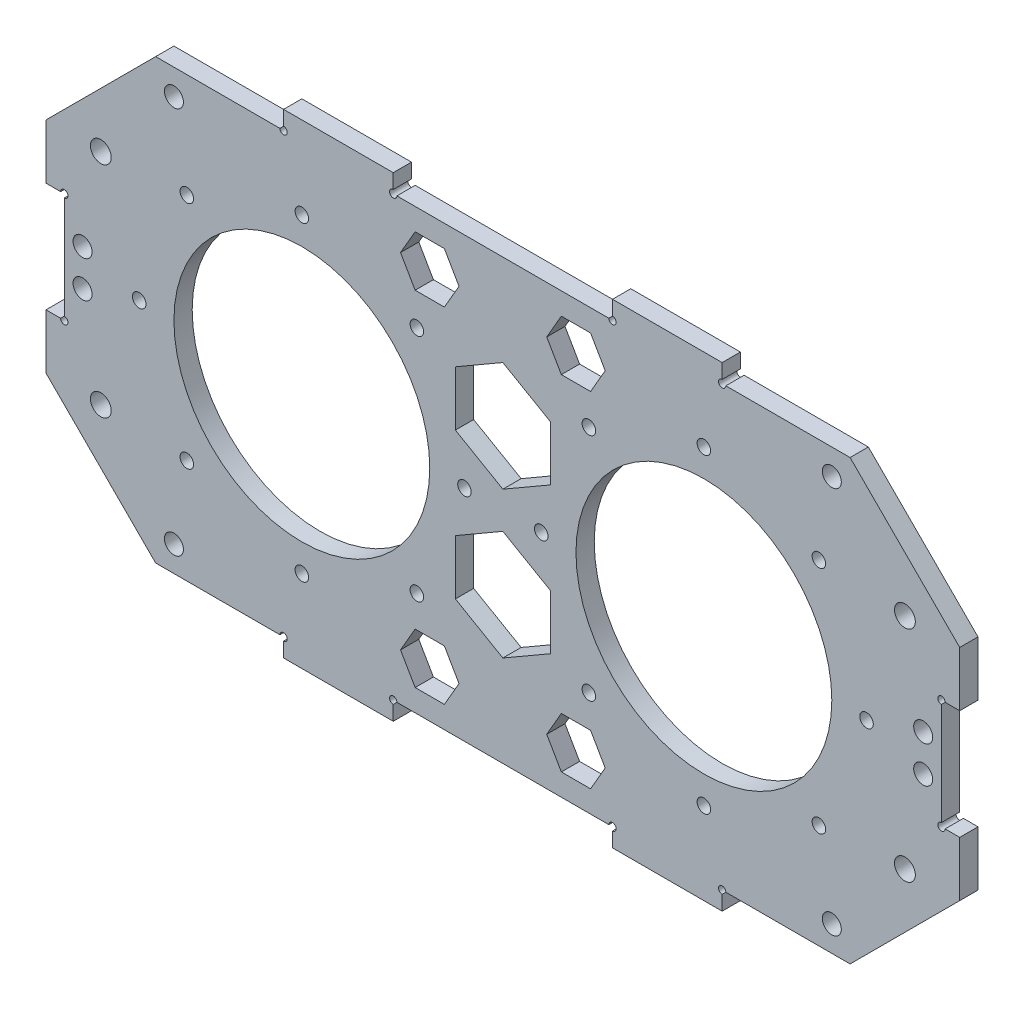
SolidWorks part; units mm, degrees
ref_plane "前视基准面" through (0, 0, 0) normal (0, 0, 1) x (1, 0, 0)
ref_plane "上视基准面" through (0, 0, 0) normal (0, 1, 0) x (1, 0, 0)
ref_plane "右视基准面" through (0, 0, 0) normal (1, 0, 0) x (0, 0, -1)
other "Configuration Table"
sketch "草图1" plane through (0, 0, 0) normal (0, 0, 1) x (1, 0, 0)
  line L1 (0, 0) -> (250, 0)
  line L2 (0, 0) -> (0, 120)
  line L3 (0, 120) -> (250, 120)
  line L4 (250, 0) -> (250, 120)
  circle A0 centre (70, 60) radius 35
  circle A1 centre (180, 60) radius 35
  dimension "D3" = 70
  dimension "D4" = 70
  dimension "D7" = 70
  dimension "D8" = 60
  dimension "D1" = 250
  dimension "D2" = 120
  dimension "D5" = 60
  dimension "D6" = 70
extrude "凸台-拉伸1" add sketch "草图1" along normal blind 5
sketch "草图2" plane through (0, 0, 5) normal (0, 0, 1) x (1, 0, 0)
  line L0 (125, 120) -> (125, 0) construction
  line L4 (0, 120) -> (0, 0)
  line L5 (0, 0) -> (250, 0)
  line L6 (250, 0) -> (250, 120)
  line L7 (250, 120) -> (0, 120)
  line L8 (0, 120) -> (0, 0)
  line L9 (0, 0) -> (250, 0)
  line L10 (250, 0) -> (250, 120)
  line L11 (250, 120) -> (0, 120)
  circle A0 centre (70, 102.5) radius 1.85
  circle A1 centre (70, 60) radius 35 construction
  circle A2 centre (70, 60) radius 35
  circle A3 centre (70, 17.5) radius 1.85
  circle A4 centre (25.5, 60) radius 1.85
  circle A5 centre (38.5337, 91.4663) radius 1.85
  circle A6 centre (70, 104.5) radius 1.85
  circle A7 centre (101.4663, 91.4663) radius 1.85
  circle A8 centre (114.5, 60) radius 1.85
  circle A9 centre (101.4663, 28.5337) radius 1.85
  circle A10 centre (70, 15.5) radius 1.85
  circle A11 centre (38.5337, 28.5337) radius 1.85
  circle A12 centre (180, 102.5) radius 1.85
  circle A13 centre (148.5337, 91.4663) radius 1.85
  circle A14 centre (135.5, 60) radius 1.85
  circle A15 centre (148.5337, 28.5337) radius 1.85
  circle A16 centre (180, 17.5) radius 1.85
  circle A17 centre (211.4663, 28.5337) radius 1.85
  circle A18 centre (224.5, 60) radius 1.85
  circle A19 centre (211.4663, 91.4663) radius 1.85
  point P14 (70, 60)
  point P30 (70, 60)
  dimension "D1" = 3.7
  dimension "D5" = 3.7
  dimension "D7" = 60
  dimension "D3" = 42.5
  dimension "D6" = 44.5
  dimension "D2" = 0
  dimension "D4" = 2
  dimension "D8" = 8
extrude "切除-拉伸1" cut sketch "草图2" against normal blind 10 contours A5 | A4 | A11 | A10 A3 | A3 A10 | A9 | A8 | A6 A0 | A0 A6 | A7 | A14 | A12 | A19 | A18 | A17 | A15 | A13 | A16
sketch "草图3" plane through (0, 0, 5) normal (0, 0, 1) x (1, 0, 0)
  line L0 (30, 120) -> (0, 90)
  line L1 (125, 120) -> (125, 0)
  line L2 (0, 60) -> (250, 60)
  line L3 (220, 120) -> (250, 90)
  line L4 (0, 120) -> (0, 0)
  line L5 (0, 0) -> (250, 0)
  line L6 (250, 0) -> (250, 120)
  line L7 (250, 120) -> (0, 120)
  line L8 (0, 120) -> (0, 0)
  line L9 (0, 0) -> (250, 0)
  line L10 (250, 0) -> (250, 120)
  line L11 (250, 120) -> (0, 120)
  line L12 (220, 0) -> (250, 30)
  line L13 (30, 0) -> (0, 30)
  line M17 (0, 120) -> (0, 0)
  line M18 (0, 0) -> (250, 0)
  line M19 (250, 0) -> (250, 120)
  line M20 (250, 120) -> (0, 120)
  dimension "D2" = 45
  dimension "D3" = 30
  dimension "D1" = 0
extrude "切除-拉伸2" cut sketch "草图3" against normal blind 10 contours L0 M20 M17 | L13 L8 M18 | L12 L9 M19 | L3 M20 M19
sketch "草图4" plane through (0, 0, 0) normal (0, 0, -1) x (-1, 0, 0)
  line L0 (-125, 120) -> (-125, 0) construction
  line L1 (-125, 65) -> (-112.0096, 72.5)
  line L2 (-112.0096, 72.5) -> (-112.0096, 87.5)
  line L3 (-112.0096, 87.5) -> (-125, 95)
  line L4 (-125, 95) -> (-137.9904, 87.5)
  line L5 (-137.9904, 87.5) -> (-137.9904, 72.5)
  line L6 (-137.9904, 72.5) -> (-125, 65)
  line L7 (-250, 60) -> (0, 60) construction
  line L8 (-220, 120) -> (-250, 90)
  line L9 (-250, 90) -> (-250, 30)
  line L10 (-250, 30) -> (-220, 0)
  line L11 (-220, 0) -> (-30, 0)
  line L12 (-30, 0) -> (0, 30)
  line L13 (0, 30) -> (0, 90)
  line L14 (0, 90) -> (-30, 120)
  line L15 (-30, 120) -> (-220, 120)
  line L16 (-220, 120) -> (-250, 90)
  line L17 (-250, 90) -> (-250, 30)
  line L18 (-250, 30) -> (-220, 0)
  line L19 (-220, 0) -> (-30, 0)
  line L20 (-30, 0) -> (0, 30)
  line L21 (0, 30) -> (0, 90)
  line L22 (0, 90) -> (-30, 120)
  line L23 (-30, 120) -> (-220, 120)
  line L24 (-109, 100.1436) -> (-113, 107.0718)
  line L25 (-137, 107.0718) -> (-141, 114)
  line L26 (-141, 114) -> (-149, 114)
  line L27 (-149, 114) -> (-153, 107.0718)
  line L28 (-153, 107.0718) -> (-149, 100.1436)
  line L29 (-149, 100.1436) -> (-141, 100.1436)
  line L30 (-141, 100.1436) -> (-137, 107.0718)
  line L31 (-101, 100.1436) -> (-109, 100.1436)
  line L32 (-97, 107.0718) -> (-101, 100.1436)
  line L33 (-101, 114) -> (-97, 107.0718)
  line L34 (-109, 114) -> (-101, 114)
  line L35 (-113, 107.0718) -> (-109, 114)
  line L36 (-137.9904, 47.5) -> (-125, 55)
  line L37 (-137.9904, 32.5) -> (-137.9904, 47.5)
  line L38 (-125, 25) -> (-137.9904, 32.5)
  line L39 (-112.0096, 32.5) -> (-125, 25)
  line L40 (-112.0096, 47.5) -> (-112.0096, 32.5)
  line L41 (-125, 55) -> (-112.0096, 47.5)
  line L42 (-101, 19.8564) -> (-109, 19.8564)
  line L43 (-97, 12.9282) -> (-101, 19.8564)
  line L44 (-101, 6) -> (-97, 12.9282)
  line L45 (-109, 6) -> (-101, 6)
  line L46 (-113, 12.9282) -> (-109, 6)
  line L47 (-109, 19.8564) -> (-113, 12.9282)
  line L48 (-141, 19.8564) -> (-137, 12.9282)
  line L49 (-149, 19.8564) -> (-141, 19.8564)
  line L50 (-153, 12.9282) -> (-149, 19.8564)
  line L51 (-149, 6) -> (-153, 12.9282)
  line L52 (-141, 6) -> (-149, 6)
  line L53 (-137, 12.9282) -> (-141, 6)
  circle A0 centre (-125, 80) radius 12.9904 construction
  circle A1 centre (-145, 107.0718) radius 6.9282 construction
  dimension "D2" = 15
  dimension "D3" = 40
  dimension "D4" = 6
  dimension "D5" = 8
  dimension "D6" = 20
  dimension "D1" = 0
extrude "切除-拉伸3" cut sketch "草图4" against normal blind 10 contours L25 L26 L27 L28 L29 L30 | L24 L35 L34 L33 L32 L31 | L1 L2 L3 L4 L5 L6 | L36 L41 L40 L39 L38 L37 | L48 L53 L52 L51 L50 L49 | L42 L47 L46 L45 L44 L43
sketch "草图6" plane through (0, 0, 5) normal (0, 0, 1) x (1, 0, 0)
  line L0 (220, 120) -> (250, 90) construction
  line L1 (250, 30) -> (250, 90) construction
  line L2 (220, 0) -> (250, 30) construction
  line L3 (30, 0) -> (220, 0) construction
  line L4 (220, 120) -> (30, 120) construction
  line L5 (30, 0) -> (0, 30) construction
  line L6 (141, 100.1436) -> (149, 100.1436)
  line L7 (137, 107.0718) -> (141, 100.1436)
  line L8 (141, 114) -> (137, 107.0718)
  line L9 (149, 114) -> (141, 114)
  line L10 (153, 107.0718) -> (149, 114)
  line L11 (149, 100.1436) -> (153, 107.0718)
  line L12 (141, 100.1436) -> (149, 100.1436)
  line L13 (137, 107.0718) -> (141, 100.1436)
  line L14 (141, 114) -> (137, 107.0718)
  line L15 (149, 114) -> (141, 114)
  line L16 (153, 107.0718) -> (149, 114)
  line L17 (149, 100.1436) -> (153, 107.0718)
  line L18 (97, 12.9282) -> (101, 6)
  line L19 (101, 19.8564) -> (97, 12.9282)
  line L20 (109, 19.8564) -> (101, 19.8564)
  line L21 (113, 12.9282) -> (109, 19.8564)
  line L22 (109, 6) -> (113, 12.9282)
  line L23 (101, 6) -> (109, 6)
  line L24 (97, 12.9282) -> (101, 6)
  line L25 (101, 19.8564) -> (97, 12.9282)
  line L26 (109, 19.8564) -> (101, 19.8564)
  line L27 (113, 12.9282) -> (109, 19.8564)
  line L28 (109, 6) -> (113, 12.9282)
  line L29 (101, 6) -> (109, 6)
  line L30 (149, 19.8564) -> (141, 19.8564)
  line L31 (153, 12.9282) -> (149, 19.8564)
  line L32 (149, 6) -> (153, 12.9282)
  line L33 (141, 6) -> (149, 6)
  line L34 (137, 12.9282) -> (141, 6)
  line L35 (141, 19.8564) -> (137, 12.9282)
  line L36 (149, 19.8564) -> (141, 19.8564)
  line L37 (153, 12.9282) -> (149, 19.8564)
  line L38 (149, 6) -> (153, 12.9282)
  line L39 (141, 6) -> (149, 6)
  line L40 (137, 12.9282) -> (141, 6)
  line L41 (141, 19.8564) -> (137, 12.9282)
  line L42 (137.9904, 32.5) -> (137.9904, 47.5)
  line L43 (125, 25) -> (137.9904, 32.5)
  line L44 (112.0096, 32.5) -> (125, 25)
  line L45 (112.0096, 47.5) -> (112.0096, 32.5)
  line L46 (125, 55) -> (112.0096, 47.5)
  line L47 (137.9904, 47.5) -> (125, 55)
  line L48 (137.9904, 32.5) -> (137.9904, 47.5)
  line L49 (125, 25) -> (137.9904, 32.5)
  line L50 (112.0096, 32.5) -> (125, 25)
  line L51 (112.0096, 47.5) -> (112.0096, 32.5)
  line L52 (125, 55) -> (112.0096, 47.5)
  line L53 (137.9904, 47.5) -> (125, 55)
  line L54 (137.9904, 72.5) -> (137.9904, 87.5)
  line L55 (125, 65) -> (137.9904, 72.5)
  line L56 (112.0096, 72.5) -> (125, 65)
  line L57 (112.0096, 87.5) -> (112.0096, 72.5)
  line L58 (125, 95) -> (112.0096, 87.5)
  line L59 (137.9904, 87.5) -> (125, 95)
  line L60 (137.9904, 72.5) -> (137.9904, 87.5)
  line L61 (125, 65) -> (137.9904, 72.5)
  line L62 (112.0096, 72.5) -> (125, 65)
  line L63 (112.0096, 87.5) -> (112.0096, 72.5)
  line L64 (125, 95) -> (112.0096, 87.5)
  line L65 (137.9904, 87.5) -> (125, 95)
  line L66 (101, 100.1436) -> (109, 100.1436)
  line L67 (97, 107.0718) -> (101, 100.1436)
  line L68 (101, 114) -> (97, 107.0718)
  line L69 (109, 114) -> (101, 114)
  line L70 (113, 107.0718) -> (109, 114)
  line L71 (109, 100.1436) -> (113, 107.0718)
  line L72 (101, 100.1436) -> (109, 100.1436)
  line L73 (97, 107.0718) -> (101, 100.1436)
  line L74 (101, 114) -> (97, 107.0718)
  line L75 (109, 114) -> (101, 114)
  line L76 (113, 107.0718) -> (109, 114)
  line L77 (109, 100.1436) -> (113, 107.0718)
  line L78 (0, 90) -> (0, 30) construction
  line L79 (30, 120) -> (0, 90) construction
  line L80 (220, 120) -> (250, 90)
  line L81 (250, 30) -> (250, 90)
  line L82 (220, 0) -> (250, 30)
  line L83 (30, 0) -> (220, 0)
  line L84 (220, 120) -> (30, 120)
  line L85 (30, 0) -> (0, 30)
  line L86 (0, 90) -> (0, 30)
  line L87 (30, 120) -> (0, 90)
  circle A1 centre (70, 60) radius 35
  circle A2 centre (70, 60) radius 35
  circle A3 centre (180, 60) radius 35
  circle A4 centre (180, 60) radius 35
  circle A5 centre (38.5337, 91.4663) radius 1.85
  circle A6 centre (38.5337, 91.4663) radius 1.85
  circle A7 centre (114.5, 60) radius 1.85
  circle A8 centre (114.5, 60) radius 1.85
  circle A9 centre (70, 102.5) radius 1.85
  circle A10 centre (70, 102.5) radius 1.85
  circle A11 centre (101.4663, 91.4663) radius 1.85
  circle A12 centre (101.4663, 91.4663) radius 1.85
  circle A13 centre (135.5, 60) radius 1.85
  circle A14 centre (135.5, 60) radius 1.85
  circle A15 centre (101.4663, 28.5337) radius 1.85
  circle A16 centre (101.4663, 28.5337) radius 1.85
  circle A17 centre (70, 17.5) radius 1.85
  circle A18 centre (70, 17.5) radius 1.85
  circle A19 centre (38.5337, 28.5337) radius 1.85
  circle A20 centre (38.5337, 28.5337) radius 1.85
  circle A21 centre (25.5, 60) radius 1.85
  circle A22 centre (25.5, 60) radius 1.85
  circle A23 centre (180, 17.5) radius 1.85
  circle A24 centre (180, 17.5) radius 1.85
  circle A25 centre (148.5337, 91.4663) radius 1.85
  circle A26 centre (148.5337, 91.4663) radius 1.85
  circle A27 centre (148.5337, 28.5337) radius 1.85
  circle A28 centre (148.5337, 28.5337) radius 1.85
  circle A29 centre (211.4663, 28.5337) radius 1.85
  circle A30 centre (211.4663, 28.5337) radius 1.85
  circle A31 centre (224.5, 60) radius 1.85
  circle A32 centre (224.5, 60) radius 1.85
  circle A33 centre (211.4663, 91.4663) radius 1.85
  circle A34 centre (211.4663, 91.4663) radius 1.85
  circle A35 centre (180, 102.5) radius 1.85
  circle A36 centre (180, 102.5) radius 1.85
  dimension "D1" = 0
  dimension "D2" = 0
  dimension "D3" = 0
  dimension "D4" = 0
  dimension "D5" = 0
  dimension "D6" = 0
  dimension "D7" = 0
  dimension "D8" = 0
  dimension "D9" = 0
  dimension "D10" = 0
  dimension "D11" = 0
  dimension "D12" = 0
  dimension "D13" = 0
  dimension "D14" = 0
  dimension "D15" = 0
  dimension "D16" = 0
  dimension "D17" = 0
  dimension "D18" = 0
  dimension "D19" = 0
  dimension "D20" = 0
  dimension "D21" = 0
  dimension "D22" = 0
  dimension "D23" = 0
  dimension "D24" = 0
sketch "草图7" plane through (0, 0, 5) normal (0, 0, 1) x (1, 0, 0)
  line L0 (125, 120) -> (125, 0) construction
  line L1 (65, 0) -> (95, 0)
  line L2 (65, 0) -> (65, -5)
  line L3 (65, -5) -> (95, -5)
  line L4 (95, 0) -> (95, -5)
  line L5 (155, 0) -> (185, 0)
  line L6 (155, 0) -> (155, -5)
  line L7 (155, -5) -> (185, -5)
  line L8 (250, 30) -> (250, 90)
  line L9 (250, 90) -> (220, 120)
  line L10 (220, 120) -> (30, 120)
  line L11 (30, 120) -> (0, 90)
  line L12 (0, 90) -> (0, 30)
  line L13 (0, 30) -> (30, 0)
  line L14 (30, 0) -> (220, 0)
  line L15 (220, 0) -> (250, 30)
  line L16 (250, 30) -> (250, 90)
  line L17 (250, 90) -> (220, 120)
  line L18 (220, 120) -> (30, 120)
  line L19 (30, 120) -> (0, 90)
  line L20 (0, 90) -> (0, 30)
  line L21 (0, 30) -> (30, 0)
  line L22 (30, 0) -> (220, 0)
  line L23 (220, 0) -> (250, 30)
  line L24 (185, 0) -> (185, -5)
  line L25 (0, 60) -> (250, 60) construction
  line L26 (185, 120) -> (185, 125)
  line L27 (155, 125) -> (185, 125)
  line L28 (155, 120) -> (155, 125)
  line L29 (95, 120) -> (95, 125)
  line L30 (65, 125) -> (95, 125)
  line L31 (65, 120) -> (65, 125)
  dimension "D2" = 30
  dimension "D3" = 5
  dimension "D4" = 30
  dimension "D5" = 30
  dimension "D6" = 5
  dimension "D7" = 30
  dimension "D1" = 0
extrude "凸台-拉伸2" add sketch "草图7" against normal blind 5 contours L31 L18 L29 L30 | L28 L18 L26 L27 | L4 L1 L2 L3 | L24 L5 L6 L7
sketch "草图8" plane through (0, 0, 5) normal (0, 0, 1) x (1, 0, 0)
  line L24 (250, 30) -> (250, 90)
  line L25 (250, 90) -> (220, 120)
  line L26 (220, 120) -> (185, 120)
  line L27 (185, 120) -> (185, 125)
  line L28 (185, 125) -> (155, 125)
  line L29 (155, 125) -> (155, 120)
  line L30 (155, 120) -> (95, 120)
  line L31 (95, 120) -> (95, 125)
  line L32 (95, 125) -> (65, 125)
  line L33 (65, 125) -> (65, 120)
  line L34 (65, 120) -> (30, 120)
  line L35 (30, 120) -> (0, 90)
  line L36 (0, 90) -> (0, 30)
  line L37 (0, 30) -> (30, 0)
  line L38 (30, 0) -> (65, 0)
  line L39 (65, 0) -> (65, -5)
  line L40 (65, -5) -> (95, -5)
  line L41 (95, -5) -> (95, 0)
  line L42 (95, 0) -> (155, 0)
  line L43 (155, 0) -> (155, -5)
  line L44 (155, -5) -> (185, -5)
  line L45 (185, -5) -> (185, 0)
  line L46 (185, 0) -> (220, 0)
  line L47 (220, 0) -> (250, 30)
  line L48 (250, 30) -> (250, 90)
  line L49 (250, 90) -> (220, 120)
  line L50 (220, 120) -> (185, 120)
  line L51 (185, 120) -> (185, 125)
  line L52 (185, 125) -> (155, 125)
  line L53 (155, 125) -> (155, 120)
  line L54 (155, 120) -> (95, 120)
  line L55 (95, 120) -> (95, 125)
  line L56 (95, 125) -> (65, 125)
  line L57 (65, 125) -> (65, 120)
  line L58 (65, 120) -> (30, 120)
  line L59 (30, 120) -> (0, 90)
  line L60 (0, 90) -> (0, 30)
  line L61 (0, 30) -> (30, 0)
  line L62 (30, 0) -> (65, 0)
  line L63 (65, 0) -> (65, -5)
  line L64 (65, -5) -> (95, -5)
  line L65 (95, -5) -> (95, 0)
  line L66 (95, 0) -> (155, 0)
  line L67 (155, 0) -> (155, -5)
  line L68 (155, -5) -> (185, -5)
  line L69 (185, -5) -> (185, 0)
  line L70 (185, 0) -> (220, 0)
  line L71 (220, 0) -> (250, 30)
  circle A0 centre (65, 0) radius 1
  circle A1 centre (95, 0) radius 1
  circle A2 centre (155, 0) radius 1
  circle A3 centre (185, 0) radius 1
  circle A4 centre (65, 120) radius 1
  circle A5 centre (95, 120) radius 1
  circle A6 centre (155, 120) radius 1
  circle A7 centre (185, 120) radius 1
  dimension "D2" = 2
  dimension "D3" = 2
  dimension "D4" = 2
  dimension "D5" = 2
  dimension "D6" = 2
  dimension "D7" = 2
  dimension "D8" = 2
  dimension "D9" = 2
  dimension "D1" = 0
extrude "切除-拉伸4" cut sketch "草图8" against normal blind 10 contours L66 A1 L65 | L67 A2 L66 | L70 A3 L69 | L54 A6 L53 | L51 A7 L50 | L58 A4 L57 | L55 A5 L54 | A0
sketch "草图9" plane through (0, 0, 5) normal (0, 0, 1) x (1, 0, 0)
  line L0 (125, 120) -> (125, 0) construction
  line L1 (0, 75) -> (5, 75)
  line L2 (0, 75) -> (0, 45)
  line L3 (0, 45) -> (5, 45)
  line L4 (5, 75) -> (5, 45)
  line L5 (250, 45) -> (245, 45)
  line L6 (245, 75) -> (245, 45)
  line L7 (250, 75) -> (250, 45)
  line L8 (250, 75) -> (245, 75)
  line L24 (30, 0) -> (64, 0)
  line L25 (65, -1) -> (65, -5)
  line L26 (65, -5) -> (95, -5)
  line L27 (95, -5) -> (95, -1)
  line L28 (96, 0) -> (154, 0)
  line L29 (155, -1) -> (155, -5)
  line L30 (155, -5) -> (185, -5)
  line L31 (185, -5) -> (185, -1)
  line L32 (186, 0) -> (220, 0)
  line L33 (220, 0) -> (250, 30)
  line L34 (250, 30) -> (250, 90)
  line L35 (250, 90) -> (220, 120)
  line L36 (220, 120) -> (186, 120)
  line L37 (185, 121) -> (185, 125)
  line L38 (185, 125) -> (155, 125)
  line L39 (155, 125) -> (155, 121)
  line L40 (154, 120) -> (96, 120)
  line L41 (95, 121) -> (95, 125)
  line L42 (95, 125) -> (65, 125)
  line L43 (65, 125) -> (65, 121)
  line L44 (64, 120) -> (30, 120)
  line L45 (30, 120) -> (0, 90)
  line L46 (0, 90) -> (0, 30)
  line L47 (0, 30) -> (30, 0)
  line L48 (30, 0) -> (64, 0)
  line L49 (65, -1) -> (65, -5)
  line L50 (65, -5) -> (95, -5)
  line L51 (95, -5) -> (95, -1)
  line L52 (96, 0) -> (154, 0)
  line L53 (155, -1) -> (155, -5)
  line L54 (155, -5) -> (185, -5)
  line L55 (185, -5) -> (185, -1)
  line L56 (186, 0) -> (220, 0)
  line L57 (220, 0) -> (250, 30)
  line L58 (250, 30) -> (250, 90)
  line L59 (250, 90) -> (220, 120)
  line L60 (220, 120) -> (186, 120)
  line L61 (185, 121) -> (185, 125)
  line L62 (185, 125) -> (155, 125)
  line L63 (155, 125) -> (155, 121)
  line L64 (154, 120) -> (96, 120)
  line L65 (95, 121) -> (95, 125)
  line L66 (95, 125) -> (65, 125)
  line L67 (65, 125) -> (65, 121)
  line L68 (64, 120) -> (30, 120)
  line L69 (30, 120) -> (0, 90)
  line L70 (0, 90) -> (0, 30)
  line L71 (0, 30) -> (30, 0)
  circle A0 centre (5, 75) radius 1
  circle A1 centre (5, 45) radius 1
  circle A2 centre (245, 75) radius 1
  circle A3 centre (245, 45) radius 1
  arc A8 (65, -1) -> (64, 0) centre (65, 0) ccw
  arc A9 (96, 0) -> (95, -1) centre (95, 0) ccw
  arc A10 (155, -1) -> (154, 0) centre (155, 0) ccw
  arc A11 (186, 0) -> (185, -1) centre (185, 0) ccw
  arc A12 (185, 121) -> (186, 120) centre (185, 120) ccw
  arc A13 (154, 120) -> (155, 121) centre (155, 120) ccw
  arc A14 (95, 121) -> (96, 120) centre (95, 120) ccw
  arc A15 (64, 120) -> (65, 121) centre (65, 120) ccw
  arc A16 (65, -1) -> (64, 0) centre (65, 0) ccw
  arc A17 (96, 0) -> (95, -1) centre (95, 0) ccw
  arc A18 (155, -1) -> (154, 0) centre (155, 0) ccw
  arc A19 (186, 0) -> (185, -1) centre (185, 0) ccw
  arc A20 (185, 121) -> (186, 120) centre (185, 120) ccw
  arc A21 (154, 120) -> (155, 121) centre (155, 120) ccw
  arc A22 (95, 121) -> (96, 120) centre (95, 120) ccw
  arc A23 (64, 120) -> (65, 121) centre (65, 120) ccw
  dimension "D5" = 2
  dimension "D6" = 2
  dimension "D7" = 2
  dimension "D8" = 2
  dimension "D2" = 5
  dimension "D3" = 30
  dimension "D4" = 15
  dimension "D1" = 0
extrude "切除-拉伸5" cut sketch "草图9" against normal blind 5 contours A1 L4 A0 L1 L2 L3 | L1 A0 L4 | L4 A0 L1 | L4 A1 L3 | L3 A1 L4 | L8 A2 L6 | A3 L5 L7 L8 A2 L6 | L6 A2 L8 | L6 A3 L5 | L5 A3 L6
sketch "草图10" plane through (0, 0, 5) normal (0, 0, 1) x (1, 0, 0)
  line L0 (60, 0) -> (60, 16.3528)
  line L1 (125, 120) -> (125, 0)
  line L2 (5, 60) -> (245, 60)
  line L32 (4, 45) -> (0, 45)
  line L33 (0, 45) -> (0, 30)
  line L34 (0, 30) -> (30, 0)
  line L35 (30, 0) -> (64, 0)
  line L36 (65, -1) -> (65, -5)
  line L37 (65, -5) -> (95, -5)
  line L38 (95, -5) -> (95, -1)
  line L39 (96, 0) -> (154, 0)
  line L40 (155, -1) -> (155, -5)
  line L41 (155, -5) -> (185, -5)
  line L42 (185, -5) -> (185, -1)
  line L43 (186, 0) -> (220, 0)
  line L44 (220, 0) -> (250, 30)
  line L45 (250, 30) -> (250, 45)
  line L46 (250, 45) -> (246, 45)
  line L47 (245, 46) -> (245, 74)
  line L48 (246, 75) -> (250, 75)
  line L49 (250, 75) -> (250, 90)
  line L50 (250, 90) -> (220, 120)
  line L51 (220, 120) -> (186, 120)
  line L52 (185, 121) -> (185, 125)
  line L53 (185, 125) -> (155, 125)
  line L54 (155, 125) -> (155, 121)
  line L55 (154, 120) -> (96, 120)
  line L56 (95, 121) -> (95, 125)
  line L57 (95, 125) -> (65, 125)
  line L58 (65, 125) -> (65, 121)
  line L59 (64, 120) -> (30, 120)
  line L60 (30, 120) -> (0, 90)
  line L61 (0, 90) -> (0, 75)
  line L62 (0, 75) -> (4, 75)
  line L63 (5, 74) -> (5, 46)
  line L64 (4, 45) -> (0, 45)
  line L65 (0, 45) -> (0, 30)
  line L66 (0, 30) -> (30, 0)
  line L67 (30, 0) -> (64, 0)
  line L68 (65, -1) -> (65, -5)
  line L69 (65, -5) -> (95, -5)
  line L70 (95, -5) -> (95, -1)
  line L71 (96, 0) -> (154, 0)
  line L72 (155, -1) -> (155, -5)
  line L73 (155, -5) -> (185, -5)
  line L74 (185, -5) -> (185, -1)
  line L75 (186, 0) -> (220, 0)
  line L76 (220, 0) -> (250, 30)
  line L77 (250, 30) -> (250, 45)
  line L78 (250, 45) -> (246, 45)
  line L79 (245, 46) -> (245, 74)
  line L80 (246, 75) -> (250, 75)
  line L81 (250, 75) -> (250, 90)
  line L82 (250, 90) -> (220, 120)
  line L83 (220, 120) -> (186, 120)
  line L84 (185, 121) -> (185, 125)
  line L85 (185, 125) -> (155, 125)
  line L86 (155, 125) -> (155, 121)
  line L87 (154, 120) -> (96, 120)
  line L88 (95, 121) -> (95, 125)
  line L89 (95, 125) -> (65, 125)
  line L90 (65, 125) -> (65, 121)
  line L91 (64, 120) -> (30, 120)
  line L92 (30, 120) -> (0, 90)
  line L93 (0, 90) -> (0, 75)
  line L94 (0, 75) -> (4, 75)
  line L95 (5, 74) -> (5, 46)
  circle A0 centre (15, 30) radius 2.85
  circle A1 centre (10, 55) radius 2.6
  circle A2 centre (35, 7) radius 2.6
  circle A3 centre (215, 7) radius 2.6
  circle A4 centre (235, 30) radius 2.85
  circle A5 centre (240, 55) radius 2.6
  circle A6 centre (240, 65) radius 2.6
  circle A7 centre (235, 90) radius 2.85
  circle A8 centre (215, 113) radius 2.6
  circle A9 centre (35, 113) radius 2.6
  circle A10 centre (15, 90) radius 2.85
  circle A11 centre (10, 65) radius 2.6
  arc A12 (4, 45) -> (5, 46) centre (5, 45) ccw
  arc A13 (65, -1) -> (64, 0) centre (65, 0) ccw
  arc A14 (96, 0) -> (95, -1) centre (95, 0) ccw
  arc A15 (155, -1) -> (154, 0) centre (155, 0) ccw
  arc A16 (186, 0) -> (185, -1) centre (185, 0) ccw
  arc A17 (245, 46) -> (246, 45) centre (245, 45) ccw
  arc A18 (246, 75) -> (245, 74) centre (245, 75) ccw
  arc A19 (185, 121) -> (186, 120) centre (185, 120) ccw
  arc A20 (154, 120) -> (155, 121) centre (155, 120) ccw
  arc A21 (95, 121) -> (96, 120) centre (95, 120) ccw
  arc A22 (64, 120) -> (65, 121) centre (65, 120) ccw
  arc A23 (5, 74) -> (4, 75) centre (5, 75) ccw
  arc A24 (4, 45) -> (5, 46) centre (5, 45) ccw
  arc A25 (65, -1) -> (64, 0) centre (65, 0) ccw
  arc A26 (96, 0) -> (95, -1) centre (95, 0) ccw
  arc A27 (155, -1) -> (154, 0) centre (155, 0) ccw
  arc A28 (186, 0) -> (185, -1) centre (185, 0) ccw
  arc A29 (245, 46) -> (246, 45) centre (245, 45) ccw
  arc A30 (246, 75) -> (245, 74) centre (245, 75) ccw
  arc A31 (185, 121) -> (186, 120) centre (185, 120) ccw
  arc A32 (154, 120) -> (155, 121) centre (155, 120) ccw
  arc A33 (95, 121) -> (96, 120) centre (95, 120) ccw
  arc A34 (64, 120) -> (65, 121) centre (65, 120) ccw
  arc A35 (5, 74) -> (4, 75) centre (5, 75) ccw
  dimension "D3" = 5.7
  dimension "D4" = 0
  dimension "D5" = 5.2
  dimension "D10" = 5.2
  dimension "D2" = 15
  dimension "D6" = 10
  dimension "D7" = 10
  dimension "D8" = 30
  dimension "D9" = 25
  dimension "D11" = 7
  dimension "D1" = 0
extrude "切除-拉伸6" cut sketch "草图10" against normal through all contours A1 | A0 | A2 | A3 | A4 | A5 | A11 | A10 | A9 | A8 | A7 | A6
